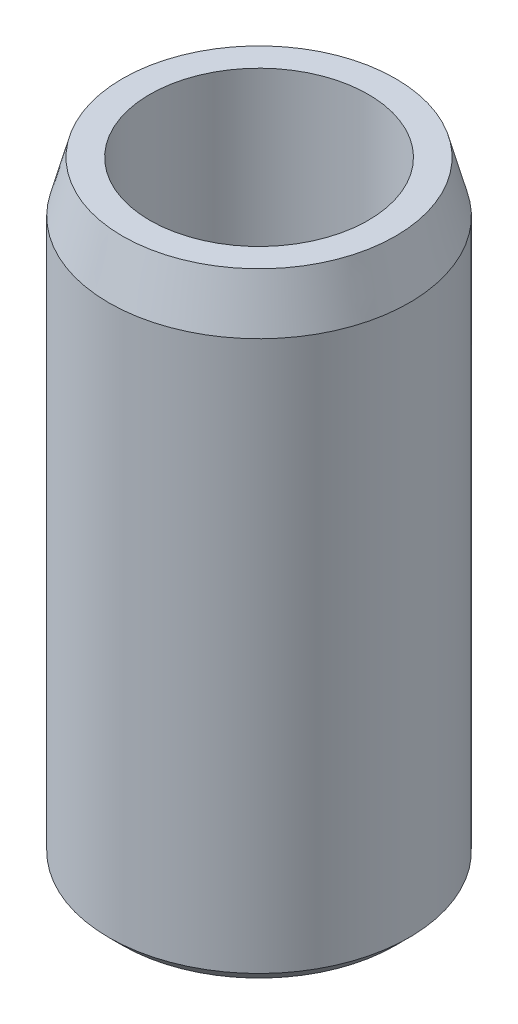
SolidWorks part; units mm, degrees
material "1.7131 (16MnCr5)"
ref_plane "Front Plane" through (0, 0, 0) normal (0, 0, 1) x (1, 0, 0)
ref_plane "Top Plane" through (0, 0, 0) normal (0, 1, 0) x (1, 0, 0)
ref_plane "Right Plane" through (0, 0, 0) normal (1, 0, 0) x (0, 0, -1)
sketch "Sketch1" plane through (0, 0, 0) normal (0, 1, 0) x (1, 0, 0)
  circle A0 centre (0, 0) radius 22
  circle A1 centre (0, 0) radius 16
  dimension "D1" = 32
  dimension "D2" = 44
extrude "Boss-Extrude1" add sketch "Sketch1" against normal blind 90
chamfer "Chamfer1" distance 2 angle 75 1 edges at (0, 0, 22)
chamfer "Chamfer2" distance 2 angle 45 1 edges at (0, -90, 22)
